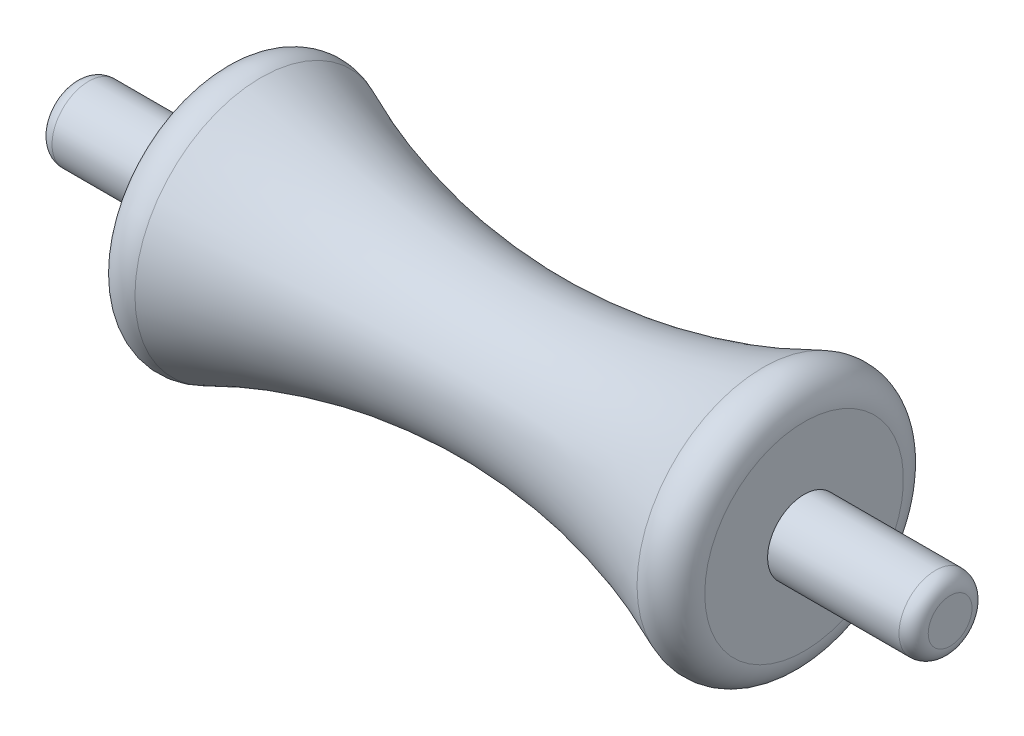
SolidWorks part; units mm, degrees
material "ABS"
ref_plane "Front Plane" through (0, 0, 0) normal (0, 0, 1) x (1, 0, 0)
ref_plane "Top Plane" through (0, 0, 0) normal (0, 1, 0) x (1, 0, 0)
ref_plane "Right Plane" through (0, 0, 0) normal (1, 0, 0) x (0, 0, -1)
sketch "Sketch3" plane through (0, 0, 0) normal (0, 0, 1) x (1, 0, 0)
  line L0 (-60, 0) -> (60, 0)
  line L1 (-60, 0) -> (-60, -3)
  line L2 (-58, -5) -> (-40, -5)
  line L3 (-40, -5) -> (-40, -13.6059)
  line L4 (0, 0) -> (0, -10) construction
  line L5 (40, -5) -> (40, -13.6059)
  line L6 (58, -5) -> (40, -5)
  line L7 (60, 0) -> (60, -3)
  arc A0 (-34.382, -17.2641) -> (34.382, -17.2641) centre (0, -95) cw
  arc A1 (58, -5) -> (60, -3) centre (58, -3) ccw
  arc A2 (-60, -3) -> (-58, -5) centre (-58, -3) ccw
  arc A3 (40, -13.6059) -> (34.382, -17.2641) centre (36, -13.6059) cw
  arc A4 (-40, -13.6059) -> (-34.382, -17.2641) centre (-36, -13.6059) ccw
  point P4 (0, 0)
  point P16 (60, -5)
  point P19 (-60, -5)
  point P22 (40, -20)
  point P25 (-40, -20)
  dimension "D6" = 2
  dimension "D7" = 4
  dimension "D1" = 120
  dimension "D2" = 5
  dimension "D3" = 20
  dimension "D4" = 15
  dimension "D5" = 10
revolve "Revolve1" add sketch "Sketch3" angle 360 about L0
